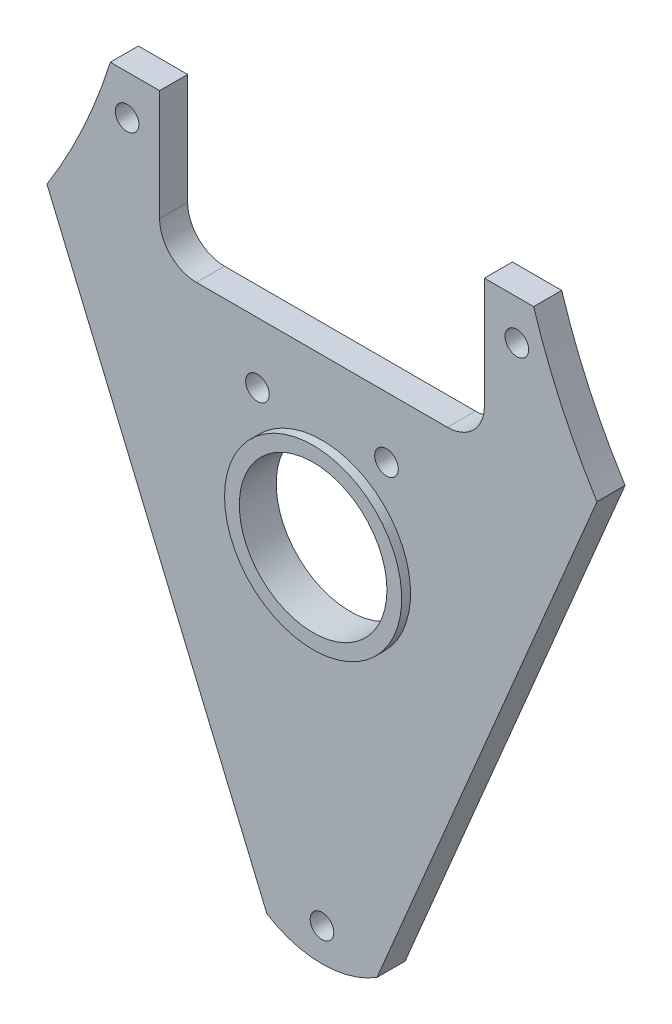
SolidWorks part; units mm, degrees
ref_plane "Front Plane" through (0, 0, 0) normal (0, 0, 1) x (1, 0, 0)
ref_plane "Top Plane" through (0, 0, 0) normal (0, 1, 0) x (1, 0, 0)
ref_plane "Right Plane" through (0, 0, 0) normal (1, 0, 0) x (0, 0, -1)
sketch "Sketch1" plane through (0, 0, 0) normal (0, 0, 1) x (1, 0, 0)
  circle A0 centre (0, 0) radius 6.35
  circle A1 centre (0, 0) radius 76.2
extrude "Boss-Extrude1" add sketch "Sketch1" along normal blind 2.413
sketch "Sketch2" plane through (0, 0, 2.413) normal (0, 0, 1) x (1, 0, 0)
  circle A0 centre (0, 0) radius 6.35
  circle A1 centre (0, 0) radius 7.62
extrude "Boss-Extrude3" add sketch "Sketch2" along normal blind 0.762
sketch "Sketch4" plane through (0, 0, 0) normal (0, 0, -1) x (-1, 0, 0)
  line L0 (-40.8208, 13.97) -> (45.303, 13.97) construction
  line L1 (-13.97, 26.67) -> (-44.6322, 26.67) construction
  line L3 (10.795, 13.97) -> (-10.795, 13.97)
  line L4 (34.2414, 26.67) -> (13.97, 26.67) construction
  line L5 (27.9769, -33.02) -> (-31.6009, -33.02) construction
  line L6 (0, 0) -> (0, -59.6584) construction
  line L7 (4.7378, -30.0359) -> (14.8903, -23.6415) construction
  line L8 (-4.7378, -30.0359) -> (-14.8903, -23.6415) construction
  line L9 (-13.97, 17.145) -> (-13.97, 26.67)
  line L10 (13.97, 17.145) -> (13.97, 26.67)
  line L14 (0, 0) -> (0, 129.5412) construction
  line L15 (-15.875, 171.4272) -> (-15.875, 41.8859) construction
  line L16 (15.875, 166.9678) -> (15.875, 41.8859) construction
  line L17 (-13.97, 26.67) -> (-18.2073, 26.67)
  line L18 (13.97, 26.67) -> (18.2073, 26.67)
  line L19 (-23.6589, 14.8628) -> (-4.7378, -30.0359)
  line L20 (23.6589, 14.8628) -> (4.7378, -30.0359)
  arc A0 (-23.6589, 14.8628) -> (-14.8903, -23.6415) centre (0, 0) ccw construction
  arc A1 (-4.7378, -30.0359) -> (4.7378, -30.0359) centre (0, -22.5136) ccw
  arc A3 (23.6589, 14.8628) -> (14.8903, -23.6415) centre (0, 0) cw construction
  circle A5 centre (0, 0) radius 76.2575
  arc A6 (-10.795, 13.97) -> (-13.97, 17.145) centre (-10.795, 17.145) cw
  arc A7 (10.795, 13.97) -> (13.97, 17.145) centre (10.795, 17.145) ccw
  arc A8 (-18.2073, 26.67) -> (-23.6589, 14.8628) centre (-66.675, 41.8859) cw
  arc A9 (18.2073, 26.67) -> (23.6589, 14.8628) centre (66.675, 41.8859) ccw
  point P21 (0, -33.02)
  point P30 (13.97, 13.97)
  dimension "D5" = 33.02
  dimension "D6" = 8.89
  dimension "D7" = 50.8
  dimension "D2" = 3.175
  dimension "D3" = 3.175
  dimension "D8" = 15.875
  dimension "D10" = 50.8
  dimension "D1" = 13.97
  dimension "D4" = 12.7
  dimension "D9" = 15.875
  dimension "D11" = 27.94
extrude "Cut-Extrude1" cut sketch "Sketch4" against normal blind 93.98
sketch "Sketch5" plane through (0, 0, 2.413) normal (0, 0, 1) x (1, 0, 0)
  line L0 (0, 0) -> (0, -44.2004) construction
  circle A0 centre (-16.764, 23.241) radius 1.016
  circle A1 centre (16.764, 23.241) radius 1.016
  circle A2 centre (0, -28.575) radius 1.016
  circle A3 centre (-5.5499, 8.7376) radius 1.016
  circle A4 centre (5.5499, 8.7376) radius 1.016
  dimension "D1" = 16.764
  dimension "D3" = 23.241
  dimension "D5" = 8.7376
  dimension "D6" = 8.7376
  dimension "D9" = 28.575
  dimension "D2" = 16.764
  dimension "D4" = 23.241
  dimension "D7" = 5.5499
  dimension "D8" = 5.5499
extrude "Cut-Extrude2" cut sketch "Sketch5" against normal blind 93.98
